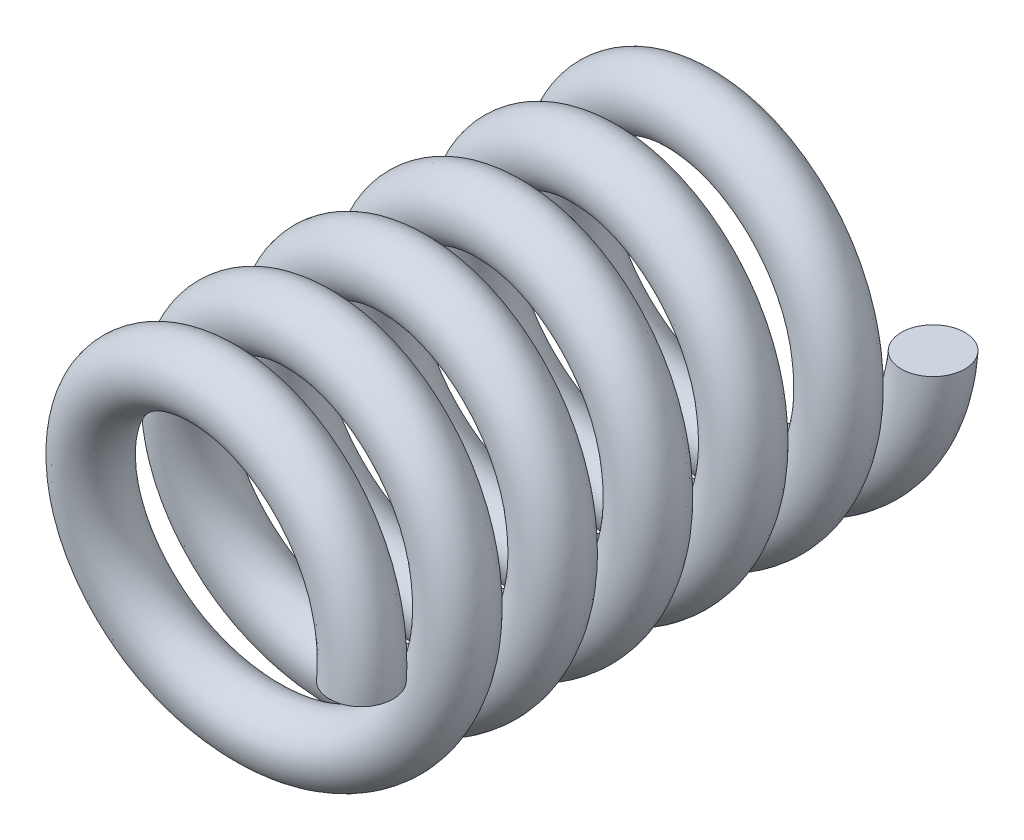
SolidWorks part; units mm, degrees
ref_plane "Front Plane" through (0, 0, 0) normal (0, 0, 1) x (1, 0, 0)
ref_plane "Top Plane" through (0, 0, 0) normal (0, 1, 0) x (1, 0, 0)
ref_plane "Right Plane" through (0, 0, 0) normal (1, 0, 0) x (0, 0, -1)
sketch "Sketch1" plane through (0, 0, 0) normal (0, 0, 1) x (1, 0, 0)
  circle A0 centre (0, 0) radius 2.5
  dimension "D1" = 5
curve "Helix/Spiral1" pitch 1.5 height 9 turns 6
sketch "Sketch2" plane through (0, 0, 0) normal (0, 1, 0) x (1, 0, 0)
  circle A0 centre (2.5, 0) radius 0.5
  spline S0 degree 3 poles (2.5, 0) (2.5, -0.0311) (2.3698, -0.0938) (1.8138, -0.1875) (0.9816, -0.2813) (0, -0.375) (-0.9816, -0.4688) (-1.8138, -0.5625) (-2.3698, -0.6563) (-2.5651, -0.75) (-2.3698, -0.8438) (-1.8138, -0.9375) (-0.7042, -1.0625) (0.7042, -1.1875) (1.8138, -1.3125) (2.3698, -1.4063) (2.5651, -1.5) (2.3698, -1.5938) (1.8138, -1.6875) (0.7042, -1.8125) (-0.7042, -1.9375) (-1.8138, -2.0625) (-2.3698, -2.1563) (-2.5651, -2.25) (-2.3698, -2.3438) (-1.8138, -2.4375) (-0.7042, -2.5625) (0.7042, -2.6875) (1.8138, -2.8125) (2.3698, -2.9063) (2.5651, -3) (2.3698, -3.0938) (1.8138, -3.1875) (0.7042, -3.3125) (-0.7042, -3.4375) (-1.8138, -3.5625) (-2.3698, -3.6563) (-2.5651, -3.75) (-2.3698, -3.8438) (-1.8138, -3.9375) (-0.7042, -4.0625) (0.7042, -4.1875) (1.8138, -4.3125) (2.3698, -4.4063) (2.5651, -4.5) (2.3698, -4.5938) (1.8138, -4.6875) (0.7042, -4.8125) (-0.7042, -4.9375) (-1.8138, -5.0625) (-2.3698, -5.1563) (-2.5651, -5.25) (-2.3698, -5.3438) (-1.8138, -5.4375) (-0.7042, -5.5625) (0.7042, -5.6875) (1.8138, -5.8125) (2.3698, -5.9063) (2.5651, -6) (2.3698, -6.0938) (1.8138, -6.1875) (0.7042, -6.3125) (-0.7042, -6.4375) (-1.8138, -6.5625) (-2.3698, -6.6563) (-2.5651, -6.75) (-2.3698, -6.8438) (-1.8138, -6.9375) (-0.7042, -7.0625) (0.7042, -7.1875) (1.8138, -7.3125) (2.3698, -7.4062) (2.5651, -7.5) (2.3698, -7.5937) (1.8138, -7.6875) (0.7042, -7.8125) (-0.7042, -7.9375) (-1.8138, -8.0625) (-2.3698, -8.1562) (-2.5651, -8.25) (-2.3698, -8.3437) (-1.8138, -8.4375) (-0.9816, -8.5312) (0, -8.625) (0.9816, -8.7187) (1.8138, -8.8125) (2.3698, -8.9062) (2.5, -8.9689) (2.5, -9) knots 0 0 0 0 0.010417 0.020833 0.03125 0.041667 0.052083 0.0625 0.072917 0.083333 0.09375 0.104167 0.114583 0.135417 0.145833 0.15625 0.166667 0.177083 0.1875 0.197917 0.21875 0.229167 0.239583 0.25 0.260417 0.270833 0.28125 0.302083 0.3125 0.322917 0.333333 0.34375 0.354167 0.364583 0.385417 0.395833 0.40625 0.416667 0.427083 0.4375 0.447917 0.46875 0.479167 0.489583 0.5 0.510417 0.520833 0.53125 0.552083 0.5625 0.572917 0.583333 0.59375 0.604167 0.614583 0.635417 0.645833 0.65625 0.666667 0.677083 0.6875 0.697917 0.71875 0.729167 0.739583 0.75 0.760417 0.770833 0.78125 0.802083 0.8125 0.822917 0.833333 0.84375 0.854167 0.864583 0.885417 0.895833 0.90625 0.916667 0.927083 0.9375 0.947917 0.958333 0.96875 0.979167 0.989583 1 1 1 1 construction
  dimension "D1" = 1
sweep "Sweep1" add profiles "Sketch2" path "Helix/Spiral1"
